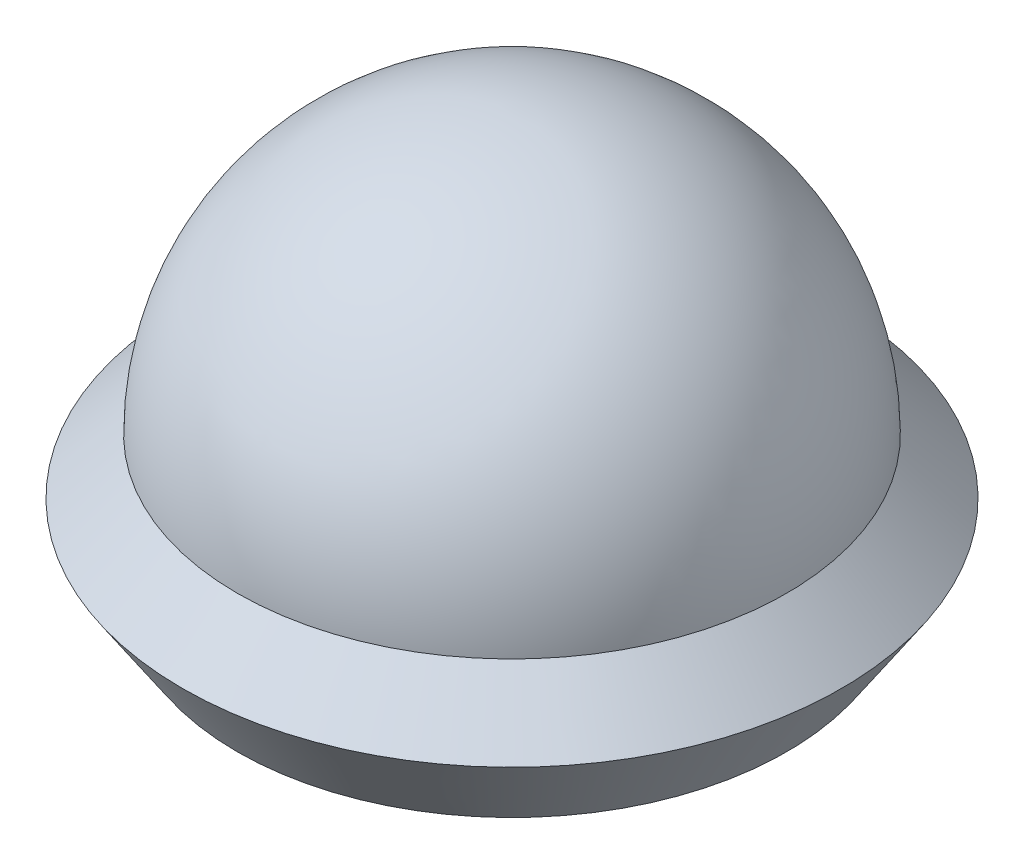
SolidWorks part; units mm, degrees
ref_plane "Plan de face" through (0, 0, 0) normal (0, 0, 1) x (1, 0, 0)
ref_plane "Plan de dessus" through (0, 0, 0) normal (0, 1, 0) x (1, 0, 0)
ref_plane "Plan de droite" through (0, 0, 0) normal (1, 0, 0) x (0, 0, -1)
sketch "Esquisse1" plane through (0, 0, 0) normal (0, 0, 1) x (1, 0, 0)
  line L0 (0, 6) -> (24, 6) construction
  line L1 (0, 0) -> (20, 0)
  line L2 (0, 0) -> (0, 10)
  line L3 (0, 10) -> (20, 10)
  line L4 (20, 0) -> (20, 10) construction
  line L5 (20, 10) -> (24, 6)
  line L6 (24, 6) -> (20, 0)
  dimension "D1" = 20
  dimension "D2" = 10
  dimension "D3" = 4
  dimension "D4" = 4
revolve "Révolution1" add sketch "Esquisse1" angle 360 about L2
sketch "Esquisse2" plane through (0, 10, 0) normal (0, 1, 0) x (1, 0, 0)
  line L0 (-20, 0) -> (20, 0)
  arc A0 (-20, 0) -> (20, 0) centre (0, 0) cw
  circle A1 centre (0, 0) radius 20 construction
  point P3 (0, 0)
revolve "Révolution2" add sketch "Esquisse2" angle 180 about L0
sketch "Esquisse3" plane through (0, 0, 0) normal (0, -1, 0) x (1, 0, 0)
  line L1 (-5.25, -2.25) -> (5.25, -2.25)
  line L2 (-5.25, -2.25) -> (-5.25, 2.25)
  line L3 (-5.25, 2.25) -> (5.25, 2.25)
  line L4 (5.25, -2.25) -> (5.25, 2.25)
  line L5 (-5.25, -2.25) -> (5.25, 2.25) construction
  line L6 (-5.25, 2.25) -> (5.25, -2.25) construction
  point P0 (0, 0)
  dimension "D1" = 4.5
  dimension "D2" = 10.5
extrude "Enlèv. mat.-Extru.1" cut sketch "Esquisse3" against normal blind 15
